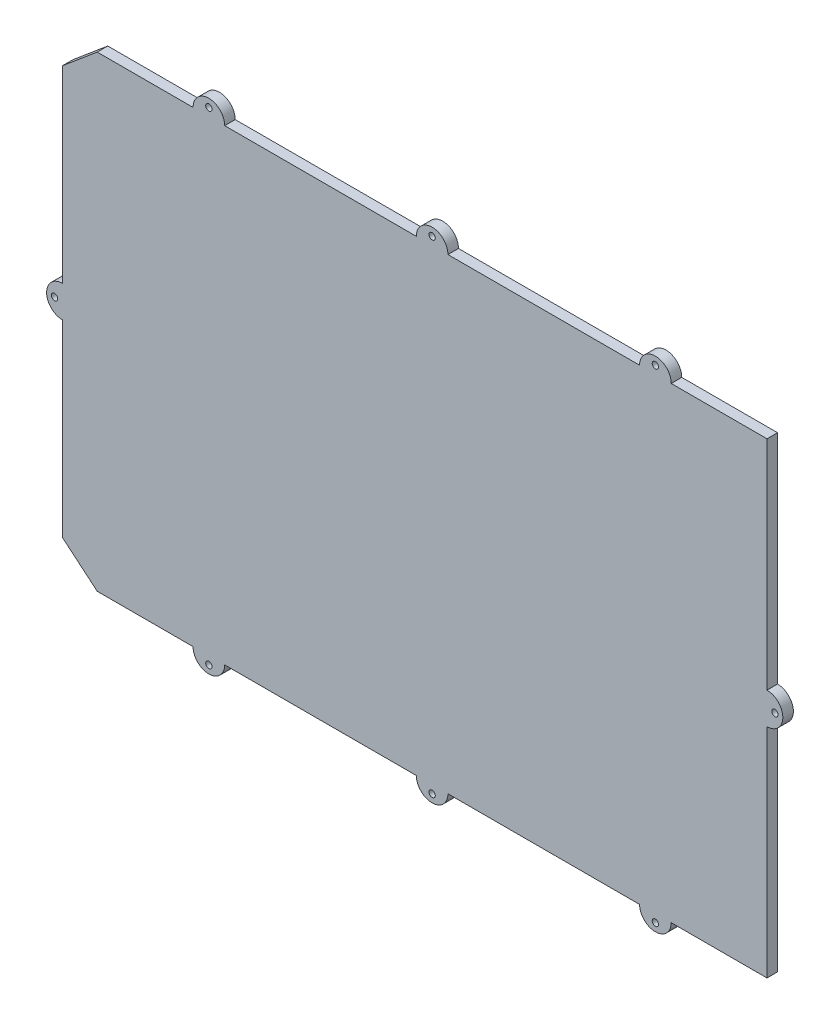
SolidWorks part; units mm, degrees
ref_plane "Front Plane" through (0, 0, 0) normal (0, 0, 1) x (1, 0, 0)
ref_plane "Top Plane" through (0, 0, 0) normal (0, 1, 0) x (1, 0, 0)
ref_plane "Right Plane" through (0, 0, 0) normal (1, 0, 0) x (0, 0, -1)
sketch "Sketch1" plane through (0, 0, 0) normal (0, 0, 1) x (1, 0, 0)
  line L0 (319.2, -227.3423) -> (319.2, -20.8423)
  line L1 (319.2, 215.6577) -> (228.3, 215.6577)
  line L2 (-316.2, 215.6577) -> (-349.2, 187.9674)
  line L3 (-349.2, 187.9674) -> (-349.2, 9.1577)
  line L4 (-349.2, -199.652) -> (-316.2, -227.3423)
  line L5 (-316.2, -227.3423) -> (-225.3, -227.3423)
  line L6 (-225.3, 215.6577) -> (-316.2, 215.6577)
  line L7 (-13.5, 215.6577) -> (-195.3, 215.6577)
  line L8 (198.3, 215.6577) -> (16.5, 215.6577)
  line L9 (-210.3, 215.6577) -> (-210.3, -227.3423) construction
  line L10 (1.5, 215.6577) -> (1.5, -227.3423) construction
  line L11 (213.3, 215.6577) -> (213.3, -227.3423) construction
  line L12 (-195.3, -227.3423) -> (-13.5, -227.3423)
  line L13 (16.5, -227.3423) -> (198.3, -227.3423)
  line L14 (228.3, -227.3423) -> (319.2, -227.3423)
  line L15 (-349.2, -20.8423) -> (-349.2, -199.652)
  line L16 (319.2, 9.1577) -> (319.2, 215.6577)
  line L17 (-210.3, 223.1577) -> (213.3, 223.1577) construction
  line L18 (-210.3, -234.8423) -> (213.3, -234.8423) construction
  arc A0 (-225.3, 215.6577) -> (-195.3, 215.6577) centre (-210.3, 215.6577) cw
  arc A1 (-13.5, 215.6577) -> (16.5, 215.6577) centre (1.5, 215.6577) cw
  arc A2 (198.3, 215.6577) -> (228.3, 215.6577) centre (213.3, 215.6577) cw
  arc A3 (-13.5, -227.3423) -> (16.5, -227.3423) centre (1.5, -227.3423) ccw
  arc A4 (-225.3, -227.3423) -> (-195.3, -227.3423) centre (-210.3, -227.3423) ccw
  arc A5 (198.3, -227.3423) -> (228.3, -227.3423) centre (213.3, -227.3423) ccw
  arc A6 (-349.2, 9.1577) -> (-349.2, -20.8423) centre (-349.2, -5.8423) ccw
  arc A7 (319.2, 9.1577) -> (319.2, -20.8423) centre (319.2, -5.8423) cw
  circle A8 centre (-210.3, 223.1577) radius 3
  circle A9 centre (1.5, 223.1577) radius 3
  circle A10 centre (213.3, 223.1577) radius 3
  circle A11 centre (326.7, -5.8423) radius 3
  circle A12 centre (-356.7, -5.8423) radius 3
  circle A13 centre (-210.3, -234.8423) radius 3
  circle A14 centre (1.5, -234.8423) radius 3
  circle A15 centre (213.3, -234.8423) radius 3
  point P47 (0, 0)
  point P48 (0, 0)
  point P49 (0, 0)
  point P51 (0, 0)
  dimension "D5" = 15
  dimension "D9" = 15
  dimension "D10" = 15
  dimension "D11" = 15
  dimension "D12" = 6
  dimension "D13" = 6
  dimension "D14" = 6
  dimension "D16" = 6
  dimension "D18" = 6
  dimension "D20" = 6
  dimension "D22" = 6
  dimension "D23" = 6
  dimension "D1" = 443
  dimension "D2" = 635.4
  dimension "D3" = 33
  dimension "D4" = 140
  dimension "D6" = 211.8
  dimension "D7" = 211.8
  dimension "D8" = 423.6
  dimension "D15" = 7.5
  dimension "D17" = 7.5
  dimension "D19" = 7.5
  dimension "D21" = 7.5
  dimension "D24" = 140
  dimension "D25" = 206.5
  dimension "D26" = 5.8423
extrude "Boss-Extrude1" add sketch "Sketch1" along normal blind 10
